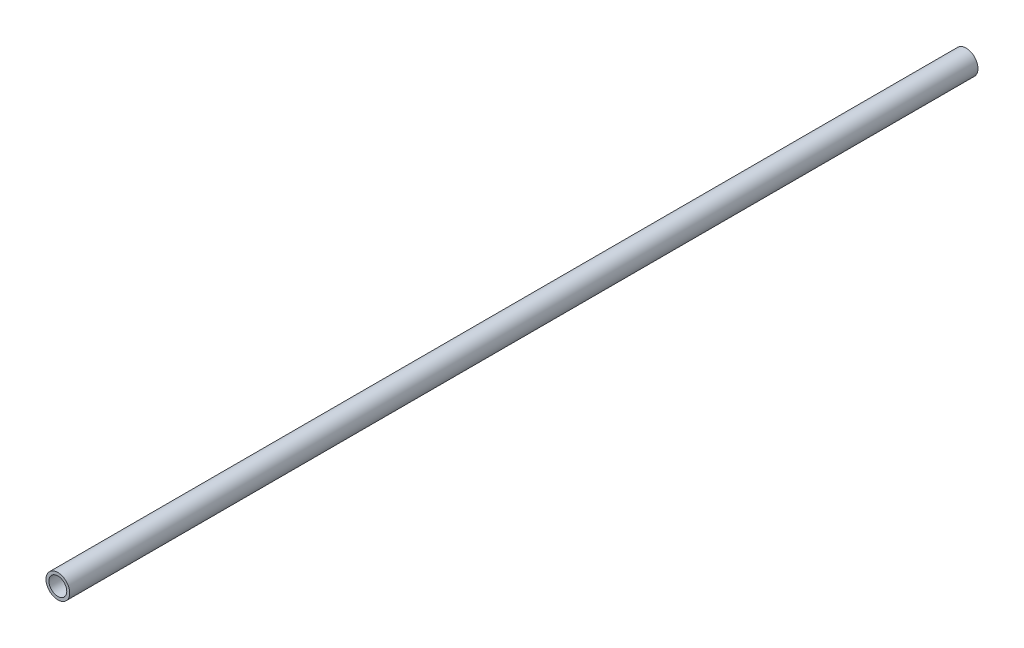
SolidWorks part; units mm, degrees
ref_plane "前视基准面" through (0, 0, 0) normal (0, 0, 1) x (1, 0, 0)
ref_plane "上视基准面" through (0, 0, 0) normal (0, 1, 0) x (1, 0, 0)
ref_plane "右视基准面" through (0, 0, 0) normal (1, 0, 0) x (0, 0, -1)
sketch "草图1" plane through (0, 0, 0) normal (0, 0, 1) x (1, 0, 0)
  circle A0 centre (0, 0) radius 4
  circle A1 centre (0, 0) radius 3
  dimension "D1" = 8
  dimension "D2" = 1
extrude "凸台-拉伸1" add sketch "草图1" along normal blind 306
